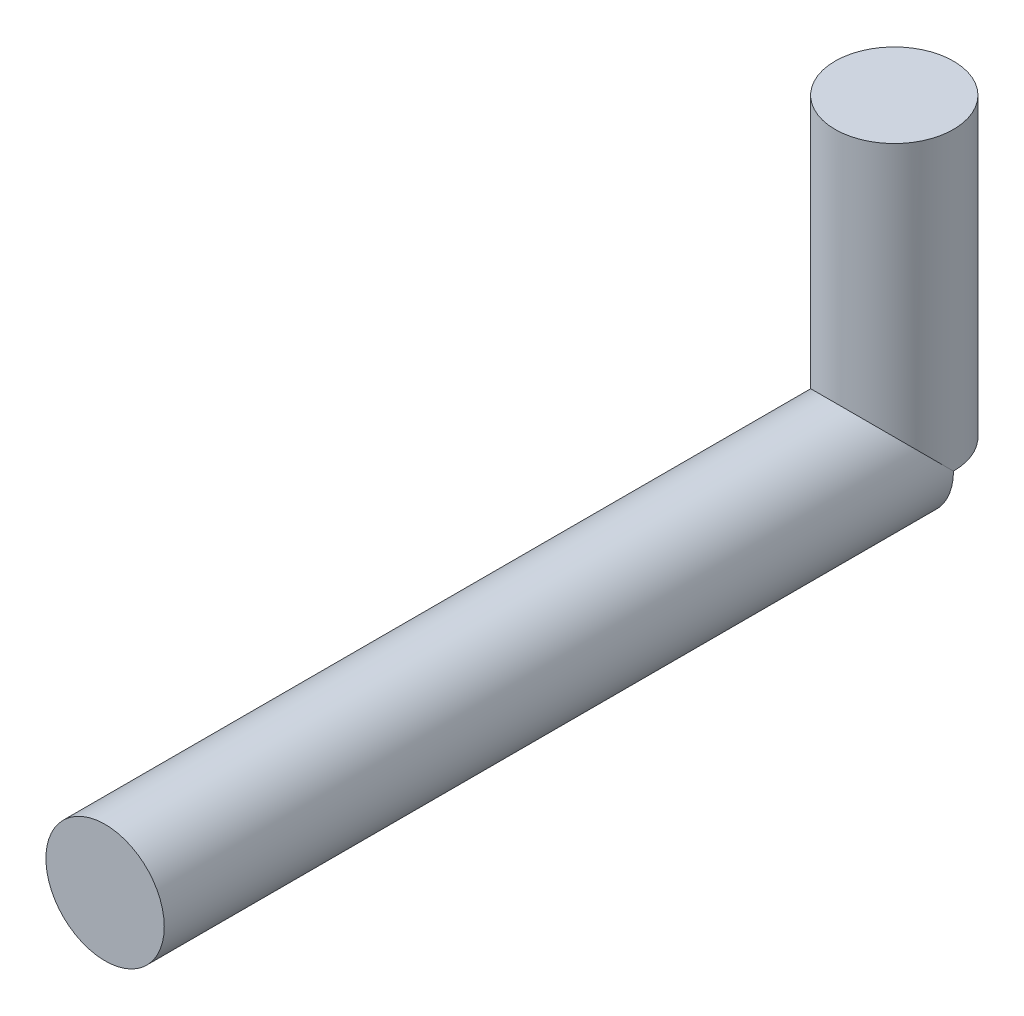
SolidWorks part; units mm, degrees
ref_plane "前视基准面" through (0, 0, 0) normal (0, 0, 1) x (1, 0, 0)
ref_plane "上视基准面" through (0, 0, 0) normal (0, 1, 0) x (1, 0, 0)
ref_plane "右视基准面" through (0, 0, 0) normal (1, 0, 0) x (0, 0, -1)
sketch "草图1" plane through (0, 0, 0) normal (0, 0, 1) x (1, 0, 0)
  line L0 (0, 0.3) -> (0, -0.3) construction
  circle A0 centre (0, 0) radius 0.3
extrude "凸台-拉伸1" add sketch "草图1" along normal blind 4
pattern_linear "阵列(线性)1" [suppressed] count 2 spacing 2.54 along (0, -1, 0)
sketch "草图2" plane through (0, 0, 0) normal (0, 1, 0) x (1, 0, 0)
  circle A0 centre (0, 0) radius 0.3
extrude "凸台-拉伸2" add sketch "草图2" along normal blind 1.5
